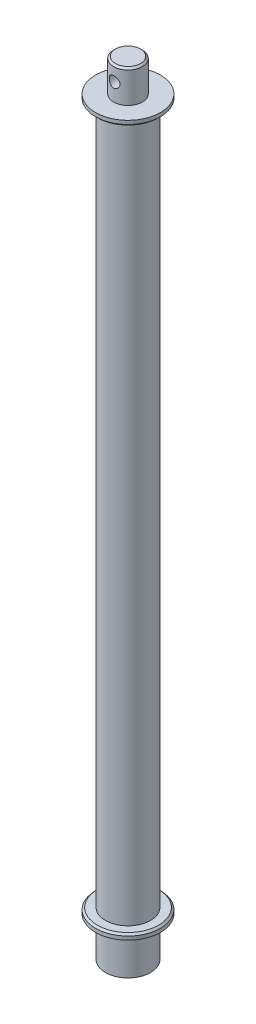
SolidWorks part; units mm, degrees
material "普通碳钢"
ref_plane "前视基准面" through (0, 0, 0) normal (0, 0, 1) x (1, 0, 0)
ref_plane "上视基准面" through (0, 0, 0) normal (0, 1, 0) x (1, 0, 0)
ref_plane "右视基准面" through (0, 0, 0) normal (1, 0, 0) x (0, 0, -1)
sketch "草图1" plane through (0, 0, 0) normal (0, 1, 0) x (1, 0, 0)
  circle A0 centre (0, 0) radius 7.95
  dimension "D1" = 15.9
extrude "凸台-拉伸1" add sketch "草图1" along normal blind 18 contours A0
sketch "草图9" plane through (0, 0, 0) normal (0, 0, 1) x (1, 0, 0)
  line L0 (0, -8.745) -> (0, 8.745) construction
  line L1 (8.745, 0) -> (-8.745, 0) construction
  circle A0 centre (0, 9.7) radius 3
  dimension "D1" = 9.7
  dimension "D2" = 6
extrude "切除-拉伸2" cut sketch "草图9" against normal through all both and the other way through all
chamfer "倒角2" distance 1 angle 45 1 edges at (0, 18, 7.95)
sketch "草图4" plane through (0, 0, 0) normal (0, 1, 0) x (1, 0, 0)
  circle A0 centre (0, 0) radius 18
extrude "凸台-拉伸2" add sketch "草图4" against normal blind 3
chamfer "倒角1" distance 1 angle 45 1 edges at (0, -3, 18)
ref_plane "基准面4" through (0, -3, 0) normal (0, -1, 0) x (-1, 0, 0)
sketch "草图5" plane through (0, -3, 0) normal (0, -1, 0) x (-1, 0, 0)
  circle A0 centre (0, 0) radius 12.5
extrude "凸台-拉伸3" add sketch "草图5" along normal blind 387.21
ref_plane "基准面5" through (0, -390.21, 0) normal (0, -1, 0) x (-1, 0, 0)
sketch "草图11" plane through (0, -390.21, 0) normal (0, -1, 0) x (-1, 0, 0)
  circle A0 centre (0, 0) radius 18
extrude "凸台-拉伸4" add sketch "草图11" along normal blind 3
chamfer "倒角3" distance 1 angle 45 1 edges at (0, -390.21, -18)
ref_plane "基准面6" through (0, -393.21, 0) normal (0, -1, 0) x (-1, 0, 0)
sketch "草图12" plane through (0, -393.21, 0) normal (0, -1, 0) x (-1, 0, 0)
  circle A0 centre (0, 0) radius 12.5
  arc A1 (1.3201, 7.2813) -> (1.0368, 7.327) centre (0, 0) ccw
  arc A2 (-0.3333, 7.3925) -> (-0.6196, 7.374) centre (0, 0) ccw
  arc A3 (-1.9699, 7.133) -> (-2.2449, 7.0513) centre (0, 0) ccw
  arc A4 (-3.5077, 6.5158) -> (-3.7577, 6.3749) centre (0, 0) ccw
  arc A5 (-4.8697, 5.5719) -> (-5.082, 5.3789) centre (0, 0) ccw
  arc A6 (-5.9875, 4.3486) -> (-6.1516, 4.1132) centre (0, 0) ccw
  arc A7 (-6.805, 2.9072) -> (-6.9126, 2.6412) centre (0, 0) ccw
  arc A8 (-7.2813, 1.3201) -> (-7.327, 1.0368) centre (0, 0) ccw
  arc A9 (-7.3925, -0.3333) -> (-7.374, -0.6196) centre (0, 0) ccw
  arc A10 (-7.133, -1.9699) -> (-7.0513, -2.2449) centre (0, 0) ccw
  arc A11 (-6.5158, -3.5077) -> (-6.3749, -3.7577) centre (0, 0) ccw
  arc A12 (-5.5719, -4.8697) -> (-5.3789, -5.082) centre (0, 0) ccw
  arc A13 (-4.3486, -5.9875) -> (-4.1132, -6.1516) centre (0, 0) ccw
  arc A14 (-2.9072, -6.805) -> (-2.6412, -6.9126) centre (0, 0) ccw
  arc A15 (-1.3201, -7.2813) -> (-1.0368, -7.327) centre (0, 0) ccw
  arc A16 (0.3333, -7.3925) -> (0.6196, -7.374) centre (0, 0) ccw
  arc A17 (1.9699, -7.133) -> (2.2449, -7.0513) centre (0, 0) ccw
  arc A18 (3.5077, -6.5158) -> (3.7577, -6.3749) centre (0, 0) ccw
  arc A19 (4.8697, -5.5719) -> (5.082, -5.3789) centre (0, 0) ccw
  arc A20 (5.9875, -4.3486) -> (6.1516, -4.1132) centre (0, 0) ccw
  arc A21 (6.805, -2.9072) -> (6.9126, -2.6412) centre (0, 0) ccw
  arc A22 (7.2813, -1.3201) -> (7.327, -1.0368) centre (0, 0) ccw
  arc A23 (7.3925, 0.3333) -> (7.374, 0.6196) centre (0, 0) ccw
  arc A24 (7.133, 1.9699) -> (7.0513, 2.2449) centre (0, 0) ccw
  arc A25 (6.5158, 3.5077) -> (6.3749, 3.7577) centre (0, 0) ccw
  arc A26 (5.5719, 4.8697) -> (5.3789, 5.082) centre (0, 0) ccw
  arc A27 (4.3486, 5.9875) -> (4.1132, 6.1516) centre (0, 0) ccw
  arc A28 (2.9072, 6.805) -> (2.6412, 6.9126) centre (0, 0) ccw
  spline S0 degree 3 poles (1.0368, 7.327) (0.9813, 7.2702) (0.9257, 7.2132) (0.8222, 7.0949) (0.7743, 7.0337) (0.6353, 6.8476) (0.5489, 6.72) (0.4775, 6.5871) knots 0 0 0 0 0.25 0.25 0.5 0.5 1 1 1 1
  spline S1 degree 3 poles (0.1466, 6.5886) (0.0874, 6.7295) (0.0225, 6.869) (-0.0958, 7.0714) (-0.1389, 7.1376) (-0.2325, 7.2668) (-0.283, 7.3297) (-0.3333, 7.3925) knots 0 0 0 0 0.5 0.5 0.75 0.75 1 1 1 1
  spline S2 degree 3 poles (-0.6196, 7.374) (-0.661, 7.3063) (-0.7026, 7.2384) (-0.7771, 7.1) (-0.81, 7.0297) (-0.9045, 6.8175) (-0.9618, 6.6745) (-1.0018, 6.5291) knots 0 0 0 0 0.25 0.25 0.5 0.5 1 1 1 1
  spline S3 degree 3 poles (-1.3247, 6.457) (-1.4136, 6.581) (-1.5073, 6.7025) (-1.6673, 6.8732) (-1.724, 6.9281) (-1.8439, 7.033) (-1.907, 7.083) (-1.9699, 7.133) knots 0 0 0 0 0.5 0.5 0.75 0.75 1 1 1 1
  spline S4 degree 3 poles (-2.2449, 7.0513) (-2.2702, 6.9761) (-2.2957, 6.9007) (-2.3374, 6.7494) (-2.3537, 6.6736) (-2.3991, 6.446) (-2.4244, 6.2939) (-2.4311, 6.1434) knots 0 0 0 0 0.25 0.25 0.5 0.5 1 1 1 1
  spline S5 degree 3 poles (-2.7298, 6.0012) (-2.8439, 6.1021) (-2.9619, 6.1997) (-3.1556, 6.3303) (-3.223, 6.3711) (-3.3629, 6.4465) (-3.4355, 6.4812) (-3.5077, 6.5158) knots 0 0 0 0 0.5 0.5 0.75 0.75 1 1 1 1
  spline S6 degree 3 poles (-3.7577, 6.3749) (-3.7657, 6.2961) (-3.7737, 6.2171) (-3.7806, 6.0606) (-3.7796, 5.9832) (-3.7736, 5.7514) (-3.7656, 5.5973) (-3.7387, 5.4493) knots 0 0 0 0 0.25 0.25 0.5 0.5 1 1 1 1
  spline S7 degree 3 poles (-3.9983, 5.2442) (-4.1317, 5.3171) (-4.2683, 5.3857) (-4.4858, 5.4696) (-4.5605, 5.4943) (-4.7134, 5.5366) (-4.7917, 5.5543) (-4.8697, 5.5719) knots 0 0 0 0 0.5 0.5 0.75 0.75 1 1 1 1
  spline S8 degree 3 poles (-5.082, 5.3789) (-5.0723, 5.3005) (-5.0626, 5.2218) (-5.0345, 5.0679) (-5.0162, 4.9928) (-4.9592, 4.7685) (-4.9181, 4.6198) (-4.8591, 4.4817) knots 0 0 0 0 0.25 0.25 0.5 0.5 1 1 1 1
  spline S9 degree 3 poles (-5.0665, 4.2239) (-5.2125, 4.2652) (-5.3608, 4.3013) (-5.5912, 4.3343) (-5.6694, 4.3418) (-5.8275, 4.349) (-5.9076, 4.3488) (-5.9875, 4.3486) knots 0 0 0 0 0.5 0.5 0.75 0.75 1 1 1 1
  spline S10 degree 3 poles (-6.1516, 4.1132) (-6.1247, 4.039) (-6.0978, 3.9646) (-6.0362, 3.8211) (-6.0017, 3.7522) (-5.8966, 3.5463) (-5.8242, 3.4102) (-5.736, 3.289) knots 0 0 0 0 0.25 0.25 0.5 0.5 1 1 1 1
  spline S11 degree 3 poles (-5.8809, 2.9915) (-6.0321, 2.9993) (-6.1847, 3.0007) (-6.4163, 2.9813) (-6.494, 2.9713) (-6.6495, 2.9432) (-6.7273, 2.9251) (-6.805, 2.9072) knots 0 0 0 0 0.5 0.5 0.75 0.75 1 1 1 1
  spline S12 degree 3 poles (-6.9126, 2.6412) (-6.87, 2.575) (-6.8273, 2.5086) (-6.7355, 2.3826) (-6.6866, 2.3232) (-6.5388, 2.1461) (-6.4383, 2.0294) (-6.3256, 1.931) knots 0 0 0 0 0.25 0.25 0.5 0.5 1 1 1 1
  spline S13 degree 3 poles (-6.4007, 1.6088) (-6.5496, 1.5827) (-6.6983, 1.5492) (-6.9194, 1.4784) (-6.9928, 1.4515) (-7.1379, 1.3897) (-7.2097, 1.3548) (-7.2813, 1.3201) knots 0 0 0 0 0.5 0.5 0.75 0.75 1 1 1 1
  spline S14 degree 3 poles (-7.327, 1.0368) (-7.2708, 0.9818) (-7.2145, 0.9267) (-7.0973, 0.8245) (-7.0365, 0.7775) (-6.8533, 0.638) (-6.7297, 0.5467) (-6.5982, 0.476) knots 0 0 0 0 0.25 0.25 0.5 0.5 1 1 1 1
  spline S15 degree 3 poles (-6.5997, 0.1451) (-6.7389, 0.0866) (-6.8759, 0.0197) (-7.0753, -0.0988) (-7.1408, -0.1413) (-7.2684, -0.2336) (-7.3305, -0.2835) (-7.3925, -0.3333) knots 0 0 0 0 0.5 0.5 0.75 0.75 1 1 1 1
  spline S16 degree 3 poles (-7.374, -0.6196) (-7.3071, -0.6606) (-7.2401, -0.7018) (-7.1033, -0.7752) (-7.0338, -0.8075) (-6.8245, -0.9025) (-6.6839, -0.9637) (-6.5402, -1.0033) knots 0 0 0 0 0.25 0.25 0.5 0.5 1 1 1 1
  spline S17 degree 3 poles (-6.468, -1.3262) (-6.5906, -1.4141) (-6.7086, -1.511) (-6.8761, -1.6712) (-6.9305, -1.727) (-7.0343, -1.8452) (-7.0837, -1.9077) (-7.133, -1.9699) knots 0 0 0 0 0.5 0.5 0.75 0.75 1 1 1 1
  spline S18 degree 3 poles (-7.0513, -2.2449) (-6.9771, -2.27) (-6.9026, -2.2952) (-6.7532, -2.3363) (-6.6783, -2.3523) (-6.4535, -2.3982) (-6.3031, -2.426) (-6.1545, -2.4326) knots 0 0 0 0 0.25 0.25 0.5 0.5 1 1 1 1
  spline S19 degree 3 poles (-6.0123, -2.7313) (-6.1121, -2.8442) (-6.2045, -2.9661) (-6.3319, -3.1598) (-6.3725, -3.2261) (-6.4474, -3.3643) (-6.4816, -3.4361) (-6.5158, -3.5077) knots 0 0 0 0 0.5 0.5 0.75 0.75 1 1 1 1
  spline S20 degree 3 poles (-6.3749, -3.7577) (-6.2971, -3.7656) (-6.219, -3.7736) (-6.0644, -3.7805) (-5.9879, -3.7795) (-5.7589, -3.774) (-5.6066, -3.7668) (-5.4604, -3.7402) knots 0 0 0 0 0.25 0.25 0.5 0.5 1 1 1 1
  spline S21 degree 3 poles (-5.2553, -3.9998) (-5.3275, -4.132) (-5.3893, -4.2723) (-5.4699, -4.4897) (-5.4948, -4.5634) (-5.5372, -4.7146) (-5.5545, -4.7923) (-5.5719, -4.8697) knots 0 0 0 0 0.5 0.5 0.75 0.75 1 1 1 1
  spline S22 degree 3 poles (-5.3789, -5.082) (-5.3014, -5.0724) (-5.2236, -5.0628) (-5.0714, -5.0353) (-4.9971, -5.0174) (-4.7754, -4.9609) (-4.6292, -4.9189) (-4.4927, -4.8606) knots 0 0 0 0 0.25 0.25 0.5 0.5 1 1 1 1
  spline S23 degree 3 poles (-4.235, -5.068) (-4.276, -5.2131) (-4.3037, -5.3642) (-4.3335, -5.5943) (-4.3416, -5.6716) (-4.3493, -5.8285) (-4.3489, -5.9081) (-4.3486, -5.9875) knots 0 0 0 0 0.5 0.5 0.75 0.75 1 1 1 1
  spline S24 degree 3 poles (-4.1132, -6.1516) (-4.0398, -6.1249) (-3.9661, -6.0982) (-3.8239, -6.0376) (-3.7554, -6.0037) (-3.5522, -5.8991) (-3.42, -5.8247) (-3.3, -5.7375) knots 0 0 0 0 0.25 0.25 0.5 0.5 1 1 1 1
  spline S25 degree 3 poles (-3.0026, -5.8824) (-3.0103, -6.0331) (-3.0024, -6.1869) (-2.9799, -6.4181) (-2.9707, -6.4953) (-2.9434, -6.6501) (-2.9252, -6.7277) (-2.9072, -6.805) knots 0 0 0 0 0.5 0.5 0.75 0.75 1 1 1 1
  spline S26 degree 3 poles (-2.6412, -6.9126) (-2.5756, -6.8703) (-2.5097, -6.8279) (-2.3845, -6.7372) (-2.3251, -6.689) (-2.1506, -6.5415) (-2.0396, -6.4388) (-1.9421, -6.3271) knots 0 0 0 0 0.25 0.25 0.5 0.5 1 1 1 1
  spline S27 degree 3 poles (-1.6199, -6.4022) (-1.5938, -6.5509) (-1.5508, -6.6993) (-1.477, -6.9199) (-1.4509, -6.9932) (-1.3899, -7.1382) (-1.3549, -7.2098) (-1.3201, -7.2813) knots 0 0 0 0 0.5 0.5 0.75 0.75 1 1 1 1
  spline S28 degree 3 poles (-1.0368, -7.327) (-0.9823, -7.2711) (-0.9275, -7.2151) (-0.8256, -7.099) (-0.7783, -7.0389) (-0.6413, -6.856) (-0.5572, -6.7303) (-0.487, -6.5997) knots 0 0 0 0 0.25 0.25 0.5 0.5 1 1 1 1
  spline S29 degree 3 poles (-0.1562, -6.6012) (-0.0976, -6.7406) (-0.0218, -6.8757) (0.0996, -7.0746) (0.1414, -7.1403) (0.2332, -7.2683) (0.2833, -7.3305) (0.3333, -7.3925) knots 0 0 0 0 0.5 0.5 0.75 0.75 1 1 1 1
  spline S30 degree 3 poles (0.6196, -7.374) (0.6604, -7.3073) (0.7013, -7.2404) (0.7751, -7.1042) (0.8079, -7.035) (0.9004, -6.8261) (0.9528, -6.6847) (0.9922, -6.5417) knots 0 0 0 0 0.25 0.25 0.5 0.5 1 1 1 1
  spline S31 degree 3 poles (1.3151, -6.4695) (1.4034, -6.5927) (1.5079, -6.7074) (1.6709, -6.8745) (1.7263, -6.9295) (1.8445, -7.034) (1.9073, -7.0836) (1.9699, -7.133) knots 0 0 0 0 0.5 0.5 0.75 0.75 1 1 1 1
  spline S32 degree 3 poles (2.2449, -7.0513) (2.2699, -6.9771) (2.2949, -6.9027) (2.3366, -6.7533) (2.3534, -6.6784) (2.3966, -6.4539) (2.4149, -6.3044) (2.4215, -6.156) knots 0 0 0 0 0.25 0.25 0.5 0.5 1 1 1 1
  spline S33 degree 3 poles (2.7202, -6.0138) (2.834, -6.1144) (2.9617, -6.2031) (3.1582, -6.33) (3.2245, -6.3713) (3.3632, -6.4471) (3.4356, -6.4815) (3.5077, -6.5158) knots 0 0 0 0 0.5 0.5 0.75 0.75 1 1 1 1
  spline S34 degree 3 poles (3.7577, -6.3749) (3.7655, -6.2969) (3.7733, -6.2187) (3.7809, -6.0635) (3.7806, -5.9867) (3.7724, -5.7579) (3.7557, -5.6082) (3.7291, -5.4619) knots 0 0 0 0 0.25 0.25 0.5 0.5 1 1 1 1
  spline S35 degree 3 poles (3.9887, -5.2568) (4.1222, -5.3297) (4.2667, -5.388) (4.4868, -5.4683) (4.5608, -5.4939) (4.7132, -5.537) (4.7916, -5.5544) (4.8697, -5.5719) knots 0 0 0 0 0.5 0.5 0.75 0.75 1 1 1 1
  spline S36 degree 3 poles (5.082, -5.3789) (5.0722, -5.301) (5.0624, -5.2229) (5.0353, -5.0696) (5.0179, -4.9946) (4.9586, -4.7732) (4.9081, -4.6312) (4.8495, -4.4942) knots 0 0 0 0 0.25 0.25 0.5 0.5 1 1 1 1
  spline S37 degree 3 poles (5.0569, -4.2365) (5.2036, -4.278) (5.3575, -4.3032) (5.5903, -4.3328) (5.6684, -4.3413) (5.8268, -4.3494) (5.9073, -4.3489) (5.9875, -4.3486) knots 0 0 0 0 0.5 0.5 0.75 0.75 1 1 1 1
  spline S38 degree 3 poles (6.1516, -4.1132) (6.1246, -4.0393) (6.0976, -3.9652) (6.0369, -3.8215) (6.0033, -3.752) (5.8957, -3.5492) (5.8142, -3.4223) (5.7265, -3.3015) knots 0 0 0 0 0.25 0.25 0.5 0.5 1 1 1 1
  spline S39 degree 3 poles (5.8714, -3.0041) (6.0238, -3.0119) (6.1796, -3.0031) (6.4136, -2.9804) (6.4917, -2.9712) (6.6483, -2.9438) (6.7268, -2.9254) (6.805, -2.9072) knots 0 0 0 0 0.5 0.5 0.75 0.75 1 1 1 1
  spline S40 degree 3 poles (6.9126, -2.6412) (6.8698, -2.5751) (6.8269, -2.5087) (6.7355, -2.3818) (6.6872, -2.3215) (6.5368, -2.1475) (6.4287, -2.042) (6.316, -1.9436) knots 0 0 0 0 0.25 0.25 0.5 0.5 1 1 1 1
  spline S41 degree 3 poles (6.3911, -1.6214) (6.5417, -1.595) (6.6919, -1.5527) (6.9154, -1.4788) (6.9896, -1.4524) (7.1364, -1.3907) (7.2089, -1.3553) (7.2813, -1.3201) knots 0 0 0 0 0.5 0.5 0.75 0.75 1 1 1 1
  spline S42 degree 3 poles (7.327, -1.0368) (7.2705, -0.9815) (7.2138, -0.9261) (7.0961, -0.8234) (7.0353, -0.7758) (6.9121, -0.6832) (6.8498, -0.6381) (6.7212, -0.5577) (6.6552, -0.5221) (6.5886, -0.4885) knots 0 0 0 0 0.25 0.25 0.5 0.5 0.75 0.75 1 1 1 1
  spline S43 degree 3 poles (6.5901, -0.1577) (6.7316, -0.0999) (6.869, -0.0256) (7.0705, 0.097) (7.1371, 0.1392) (7.2668, 0.232) (7.3297, 0.2827) (7.3925, 0.3333) knots 0 0 0 0 0.5 0.5 0.75 0.75 1 1 1 1
  spline S44 degree 3 poles (7.374, 0.6196) (7.3065, 0.661) (7.2387, 0.7025) (7.1006, 0.7767) (7.0304, 0.8093) (6.8189, 0.9046) (6.6764, 0.9634) (6.5306, 0.9907) knots 0 0 0 0 0.25 0.25 0.5 0.5 1 1 1 1
  spline S45 degree 3 poles (6.4585, 1.3136) (6.583, 1.403) (6.7015, 1.5041) (6.8717, 1.6671) (6.9271, 1.7234) (7.0327, 1.8432) (7.0829, 1.9067) (7.133, 1.9699) knots 0 0 0 0 0.5 0.5 0.75 0.75 1 1 1 1
  spline S46 degree 3 poles (7.0513, 2.2449) (6.9761, 2.2701) (6.9008, 2.2954) (6.7495, 2.3377) (6.6737, 2.3548) (6.4464, 2.3973) (6.2952, 2.4133) (6.1449, 2.42) knots 0 0 0 0 0.25 0.25 0.5 0.5 1 1 1 1
  spline S47 degree 3 poles (6.0027, 2.7188) (6.1043, 2.8336) (6.1983, 2.9576) (6.3284, 3.154) (6.3699, 3.2214) (6.4462, 3.3619) (6.481, 3.4349) (6.5158, 3.5077) knots 0 0 0 0 0.5 0.5 0.75 0.75 1 1 1 1
  spline S48 degree 3 poles (6.3749, 3.7577) (6.296, 3.7655) (6.2168, 3.7735) (6.0597, 3.781) (5.9819, 3.7807) (5.7505, 3.7717) (5.599, 3.7546) (5.4508, 3.7276) knots 0 0 0 0 0.25 0.25 0.5 0.5 1 1 1 1
  spline S49 degree 3 poles (5.2457, 3.9872) (5.3192, 4.1218) (5.3845, 4.2628) (5.468, 4.483) (5.4934, 4.558) (5.5364, 4.712) (5.5542, 4.791) (5.5719, 4.8697) knots 0 0 0 0 0.5 0.5 0.75 0.75 1 1 1 1
  spline S50 degree 3 poles (5.3789, 5.082) (5.3001, 5.0721) (5.2211, 5.0622) (5.0662, 5.0345) (4.9904, 5.0168) (4.7664, 4.9568) (4.6218, 4.9073) (4.4832, 4.848) knots 0 0 0 0 0.25 0.25 0.5 0.5 1 1 1 1
  spline S51 degree 3 poles (4.2254, 5.0554) (4.2671, 5.203) (4.3006, 5.3543) (4.3336, 5.5873) (4.3415, 5.6661) (4.3491, 5.8258) (4.3488, 5.9068) (4.3486, 5.9875) knots 0 0 0 0 0.5 0.5 0.75 0.75 1 1 1 1
  spline S52 degree 3 poles (4.1132, 6.1516) (4.0385, 6.1243) (3.9636, 6.0971) (3.8187, 6.0355) (3.7489, 6.0013) (3.5435, 5.8932) (3.4125, 5.8137) (3.2905, 5.725) knots 0 0 0 0 0.25 0.25 0.5 0.5 1 1 1 1
  spline S53 degree 3 poles (2.993, 5.8699) (3.0009, 6.0229) (3.001, 6.1775) (2.9817, 6.4118) (2.9718, 6.4903) (2.9436, 6.6476) (2.9253, 6.7264) (2.9072, 6.805) knots 0 0 0 0 0.5 0.5 0.75 0.75 1 1 1 1
  spline S54 degree 3 poles (2.6412, 6.9126) (2.5745, 6.8695) (2.5075, 6.8263) (2.38, 6.7339) (2.3196, 6.6849) (2.143, 6.534) (2.0318, 6.4282) (1.9325, 6.3145) knots 0 0 0 0 0.25 0.25 0.5 0.5 1 1 1 1
  spline S55 degree 3 poles (1.6103, 6.3896) (1.5839, 6.5404) (1.5508, 6.691) (1.4802, 6.9149) (1.453, 6.9892) (1.3905, 7.1361) (1.3552, 7.2088) (1.3201, 7.2813) knots 0 0 0 0 0.5 0.5 0.75 0.75 1 1 1 1
  spline S56 degree 3 poles (0.4775, 6.5871) (0.4657, 6.56) (0.447, 6.5346) (0.3926, 6.4942) (0.3549, 6.4794) (0.2744, 6.4783) (0.2342, 6.4929) (0.1775, 6.5346) (0.1584, 6.5609) (0.1466, 6.5886) knots 0 0 0 0 0.25 0.25 0.5 0.5 0.75 0.75 1 1 1 1
  spline S57 degree 3 poles (-1.0018, 6.5291) (-1.0073, 6.5001) (-1.0199, 6.4712) (-1.0639, 6.4196) (-1.0973, 6.3968) (-1.1756, 6.3779) (-1.218, 6.3832) (-1.2826, 6.4111) (-1.3071, 6.4326) (-1.3247, 6.457) knots 0 0 0 0 0.25 0.25 0.5 0.5 0.75 0.75 1 1 1 1
  spline S58 degree 3 poles (-2.4311, 6.1434) (-2.4299, 6.1139) (-2.4358, 6.0829) (-2.4672, 6.0228) (-2.4947, 5.9931) (-2.5668, 5.9573) (-2.6094, 5.953) (-2.6785, 5.9659) (-2.7072, 5.9813) (-2.7298, 6.0012) knots 0 0 0 0 0.25 0.25 0.5 0.5 0.75 0.75 1 1 1 1
  spline S59 degree 3 poles (-3.7387, 5.4493) (-3.731, 5.4208) (-3.7298, 5.3893) (-3.7471, 5.3237) (-3.7673, 5.2887) (-3.8296, 5.2377) (-3.8702, 5.224) (-3.9404, 5.2212) (-3.9718, 5.2299) (-3.9983, 5.2442) knots 0 0 0 0 0.25 0.25 0.5 0.5 0.75 0.75 1 1 1 1
  spline S60 degree 3 poles (-4.8591, 4.4817) (-4.8452, 4.4555) (-4.837, 4.4251) (-4.8393, 4.3573) (-4.8512, 4.3187) (-4.9006, 4.2551) (-4.9371, 4.2327) (-5.005, 4.2144) (-5.0375, 4.2158) (-5.0665, 4.2239) knots 0 0 0 0 0.25 0.25 0.5 0.5 0.75 0.75 1 1 1 1
  spline S61 degree 3 poles (-5.736, 3.289) (-5.7167, 3.2666) (-5.7019, 3.2387) (-5.6891, 3.1722) (-5.6921, 3.1318) (-5.7261, 3.0588) (-5.7567, 3.0289) (-5.8188, 2.9959) (-5.8508, 2.9901) (-5.8809, 2.9915) knots 0 0 0 0 0.25 0.25 0.5 0.5 0.75 0.75 1 1 1 1
  spline S62 degree 3 poles (-6.3256, 1.931) (-6.3017, 1.9135) (-6.2812, 1.8896) (-6.2538, 1.8276) (-6.2478, 1.7876) (-6.2647, 1.7088) (-6.2879, 1.6729) (-6.3411, 1.6269) (-6.371, 1.6141) (-6.4007, 1.6088) knots 0 0 0 0 0.25 0.25 0.5 0.5 0.75 0.75 1 1 1 1
  spline S63 degree 3 poles (-6.5982, 0.476) (-6.5716, 0.4636) (-6.5469, 0.4446) (-6.5075, 0.3902) (-6.4933, 0.3528) (-6.4923, 0.2735) (-6.5062, 0.2338) (-6.5468, 0.1769) (-6.5725, 0.1574) (-6.5997, 0.1451) knots 0 0 0 0 0.25 0.25 0.5 0.5 0.75 0.75 1 1 1 1
  spline S64 degree 3 poles (-6.5402, -1.0033) (-6.5113, -1.0091) (-6.4827, -1.0219) (-6.4318, -1.0661) (-6.4093, -1.0994) (-6.3905, -1.1771) (-6.3955, -1.2192) (-6.4229, -1.2837) (-6.444, -1.3083) (-6.468, -1.3262) knots 0 0 0 0 0.25 0.25 0.5 0.5 0.75 0.75 1 1 1 1
  spline S65 degree 3 poles (-6.1545, -2.4326) (-6.125, -2.4315) (-6.0941, -2.4375) (-6.0342, -2.469) (-6.0046, -2.4965) (-5.9688, -2.5684) (-5.9645, -2.6109) (-5.9772, -2.68) (-5.9925, -2.7087) (-6.0123, -2.7313) knots 0 0 0 0 0.25 0.25 0.5 0.5 0.75 0.75 1 1 1 1
  spline S66 degree 3 poles (-5.4604, -3.7402) (-5.4318, -3.7324) (-5.4003, -3.7312) (-5.3347, -3.7484) (-5.2996, -3.7686) (-5.2485, -3.831) (-5.2349, -3.8716) (-5.2321, -3.9419) (-5.2409, -3.9733) (-5.2553, -3.9998) knots 0 0 0 0 0.25 0.25 0.5 0.5 0.75 0.75 1 1 1 1
  spline S67 degree 3 poles (-4.4927, -4.8606) (-4.4666, -4.8465) (-4.4362, -4.8382) (-4.3683, -4.8403) (-4.3295, -4.8522) (-4.2657, -4.9017) (-4.2434, -4.9383) (-4.2252, -5.0064) (-4.2268, -5.039) (-4.235, -5.068) knots 0 0 0 0 0.25 0.25 0.5 0.5 0.75 0.75 1 1 1 1
  spline S68 degree 3 poles (-3.3, -5.7375) (-3.2777, -5.7181) (-3.2498, -5.7032) (-3.1832, -5.6902) (-3.1428, -5.6931) (-3.0696, -5.7272) (-3.0397, -5.7579) (-3.0067, -5.8202) (-3.001, -5.8523) (-3.0026, -5.8824) knots 0 0 0 0 0.25 0.25 0.5 0.5 0.75 0.75 1 1 1 1
  spline S69 degree 3 poles (-1.9421, -6.3271) (-1.9246, -6.3033) (-1.9007, -6.2827) (-1.8387, -6.2554) (-1.7987, -6.2493) (-1.72, -6.2662) (-1.684, -6.2893) (-1.638, -6.3426) (-1.6252, -6.3725) (-1.6199, -6.4022) knots 0 0 0 0 0.25 0.25 0.5 0.5 0.75 0.75 1 1 1 1
  spline S70 degree 3 poles (-0.487, -6.5997) (-0.4751, -6.5727) (-0.4563, -6.5476) (-0.4019, -6.5074) (-0.3644, -6.4928) (-0.2843, -6.4917) (-0.2441, -6.5061) (-0.1873, -6.5474) (-0.1681, -6.5736) (-0.1562, -6.6012) knots 0 0 0 0 0.25 0.25 0.5 0.5 0.75 0.75 1 1 1 1
  spline S71 degree 3 poles (0.9922, -6.5417) (0.9977, -6.5126) (1.0103, -6.4837) (1.0543, -6.4322) (1.0876, -6.4094) (1.1659, -6.3904) (1.2084, -6.3957) (1.273, -6.4237) (1.2975, -6.4451) (1.3151, -6.4695) knots 0 0 0 0 0.25 0.25 0.5 0.5 0.75 0.75 1 1 1 1
  spline S72 degree 3 poles (2.4215, -6.156) (2.4204, -6.1264) (2.4261, -6.0958) (2.4577, -6.0353) (2.4851, -6.0057) (2.5574, -5.9698) (2.5995, -5.9655) (2.669, -5.9784) (2.6976, -5.9939) (2.7202, -6.0138) knots 0 0 0 0 0.25 0.25 0.5 0.5 0.75 0.75 1 1 1 1
  spline S73 degree 3 poles (3.7291, -5.4619) (3.7214, -5.4333) (3.7202, -5.4018) (3.7375, -5.3364) (3.7577, -5.3013) (3.82, -5.2503) (3.8605, -5.2366) (3.9308, -5.2337) (3.9622, -5.2424) (3.9887, -5.2568) knots 0 0 0 0 0.25 0.25 0.5 0.5 0.75 0.75 1 1 1 1
  spline S74 degree 3 poles (4.8495, -4.4942) (4.8356, -4.4681) (4.8274, -4.4378) (4.8298, -4.3696) (4.8414, -4.3315) (4.8916, -4.267) (4.9276, -4.2453) (4.9954, -4.2269) (5.028, -4.2284) (5.0569, -4.2365) knots 0 0 0 0 0.25 0.25 0.5 0.5 0.75 0.75 1 1 1 1
  spline S75 degree 3 poles (5.7265, -3.3015) (5.7071, -3.2791) (5.6924, -3.2513) (5.6795, -3.1848) (5.6826, -3.1442) (5.7167, -3.0712) (5.7469, -3.0416) (5.8094, -3.0084) (5.8413, -3.0027) (5.8714, -3.0041) knots 0 0 0 0 0.25 0.25 0.5 0.5 0.75 0.75 1 1 1 1
  spline S76 degree 3 poles (6.316, -1.9436) (6.2922, -1.9261) (6.2717, -1.9022) (6.2443, -1.8403) (6.2382, -1.8001) (6.2552, -1.7213) (6.2781, -1.6856) (6.3316, -1.6393) (6.3615, -1.6267) (6.3911, -1.6214) knots 0 0 0 0 0.25 0.25 0.5 0.5 0.75 0.75 1 1 1 1
  spline S77 degree 3 poles (6.5886, -0.4885) (6.5615, -0.4767) (6.5362, -0.458) (6.4957, -0.4037) (6.4809, -0.3663) (6.4798, -0.2851) (6.4942, -0.2456) (6.5362, -0.1883) (6.5624, -0.1694) (6.5901, -0.1577) knots 0 0 0 0 0.25 0.25 0.5 0.5 0.75 0.75 1 1 1 1
  spline S78 degree 3 poles (6.5306, 0.9907) (6.5015, 0.9962) (6.4726, 1.0088) (6.4211, 1.0529) (6.3983, 1.0863) (6.3794, 1.1647) (6.3845, 1.2065) (6.4127, 1.2718) (6.4341, 1.296) (6.4585, 1.3136) knots 0 0 0 0 0.25 0.25 0.5 0.5 0.75 0.75 1 1 1 1
  spline S79 degree 3 poles (6.1449, 2.42) (6.1154, 2.4189) (6.0844, 2.4247) (6.0244, 2.4562) (5.9947, 2.4836) (5.9588, 2.5558) (5.9545, 2.5983) (5.9674, 2.6675) (5.9828, 2.6961) (6.0027, 2.7188) knots 0 0 0 0 0.25 0.25 0.5 0.5 0.75 0.75 1 1 1 1
  spline S80 degree 3 poles (5.4508, 3.7276) (5.4223, 3.7199) (5.3908, 3.7187) (5.3253, 3.736) (5.2902, 3.7562) (5.2392, 3.8185) (5.2255, 3.8589) (5.2227, 3.9296) (5.2314, 3.9607) (5.2457, 3.9872) knots 0 0 0 0 0.25 0.25 0.5 0.5 0.75 0.75 1 1 1 1
  spline S81 degree 3 poles (4.4832, 4.848) (4.4571, 4.8341) (4.4267, 4.826) (4.359, 4.8282) (4.3204, 4.8401) (4.2568, 4.8893) (4.2344, 4.9258) (4.2159, 4.9937) (4.2173, 5.0264) (4.2254, 5.0554) knots 0 0 0 0 0.25 0.25 0.5 0.5 0.75 0.75 1 1 1 1
  spline S82 degree 3 poles (3.2905, 5.725) (3.2681, 5.7056) (3.2402, 5.6909) (3.1737, 5.678) (3.1334, 5.681) (3.0604, 5.715) (3.0304, 5.7456) (2.9974, 5.8077) (2.9916, 5.8398) (2.993, 5.8699) knots 0 0 0 0 0.25 0.25 0.5 0.5 0.75 0.75 1 1 1 1
  spline S83 degree 3 poles (1.9325, 6.3145) (1.915, 6.2907) (1.8911, 6.2701) (1.8291, 6.2428) (1.7891, 6.2367) (1.7104, 6.2536) (1.6744, 6.2768) (1.6284, 6.33) (1.6156, 6.36) (1.6103, 6.3896) knots 0 0 0 0 0.25 0.25 0.5 0.5 0.75 0.75 1 1 1 1
extrude "凸台-拉伸5" add sketch "草图12" along normal blind 22
